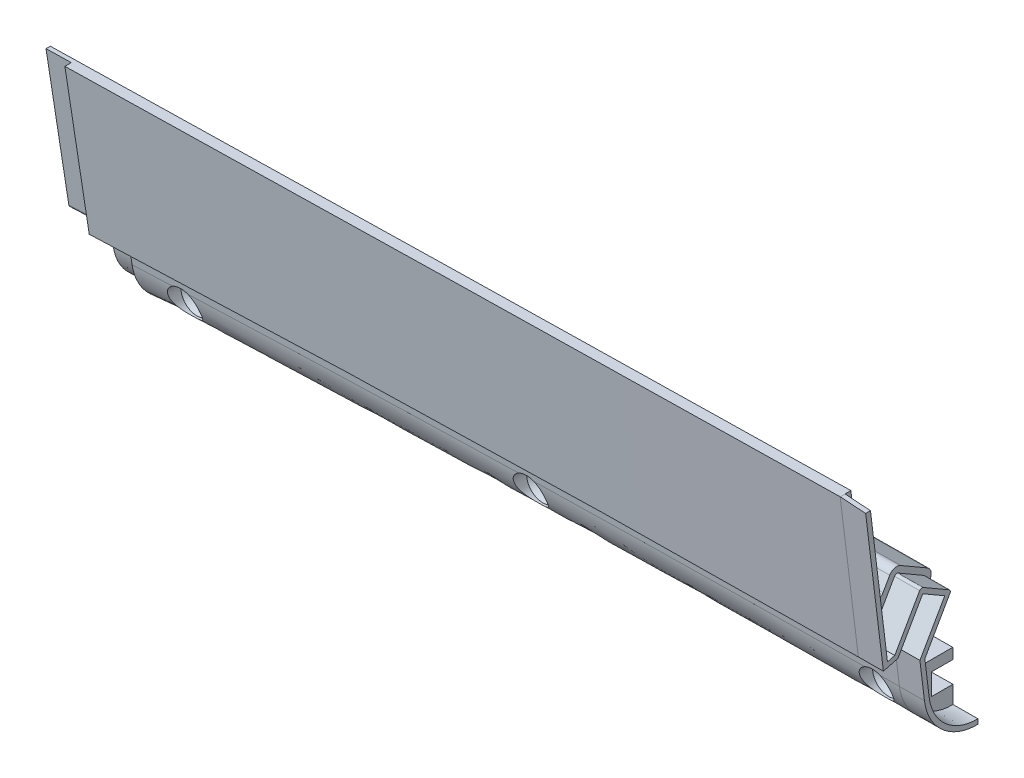
SolidWorks part; units mm, degrees
ref_plane "Front Plane" through (0, 0, 0) normal (0, 0, 1) x (1, 0, 0)
ref_plane "Top Plane" through (0, 0, 0) normal (0, 1, 0) x (1, 0, 0)
ref_plane "Right Plane" through (0, 0, 0) normal (1, 0, 0) x (0, 0, -1)
ref_plane "Plane3" through (-117.056, -3.871, 0) normal (0.9995, 0.0331, 0) x (0, 0, -1)
sketch "Sketch2" plane through (-117.056, -3.871, 0) normal (0.9995, 0.0331, 0) x (0, 0, -1)
  line L0 (-101.6, -41.1511) -> (-101.6, -45.9265)
  line L1 (-101.6, -41.1511) -> (-101.6, -45.9265)
  line L2 (-106.68, -45.9265) -> (-106.68, -50.6257)
  line L3 (-106.68, -45.9265) -> (-106.68, -50.6257)
  line L4 (-101.6, -50.6257) -> (-106.68, -50.6257)
  line L5 (-101.6, -50.6257) -> (-106.68, -50.6257)
  line L6 (-101.6, -50.6257) -> (-101.6, -56.1377)
  line L7 (-101.6, -50.6257) -> (-101.6, -56.1377)
  line L8 (-106.68, -45.9265) -> (-101.6, -45.9265)
  line L9 (-106.68, -45.9265) -> (-101.6, -45.9265)
  line L10 (-106.8705, -50.8162) -> (-108.9961, -53.9781) construction
  line L11 (-101.7905, -43.196) -> (-101.7905, -45.736)
  line L12 (-106.8705, -45.736) -> (-101.7905, -45.736)
  line L13 (-106.8705, -45.736) -> (-106.8705, -50.8162)
  line L14 (-101.7905, -50.8162) -> (-106.8705, -50.8162)
  line L15 (-101.7905, -50.8162) -> (-101.7905, -56.1377)
  line L16 (-101.7905, -43.196) -> (-101.6, -43.196)
  line L17 (-101.7905, -41.1511) -> (-101.7905, -45.736) construction
  line L18 (-120.8053, -33.0481) -> (-115.57, -36.0708)
  line L19 (-120.8053, -33.0481) -> (-115.57, -36.0708)
  line L20 (-109.601, -25.7318) -> (-114.8363, -22.709)
  line L21 (-109.601, -25.7318) -> (-114.8363, -22.709)
  line L22 (-114.8363, -22.709) -> (-120.8053, -33.0481)
  line L23 (-114.8363, -22.709) -> (-120.8053, -33.0481)
  line L24 (-115.57, -36.0708) -> (-109.601, -25.7318)
  line L25 (-115.57, -36.0708) -> (-109.601, -25.7318)
  line L26 (-115.57, -36.0708) -> (-114.523, -44.9291)
  line L28 (-118.1876, -34.5595) -> (-112.2186, -24.2204) construction
  line L29 (-114.6403, -39.5406) -> (-107.0838, -26.4518)
  line L30 (-107.7811, -23.8496) -> (-114.1162, -20.1918)
  line L31 (-116.7185, -20.8891) -> (-124.2749, -33.9778)
  line L33 (-106.1314, -24.8021) -> (-115.766, -19.2393) construction
  line L34 (-115.766, -19.2393) -> (-124.2749, -33.9778) construction
  line L35 (-114.6403, -39.5406) -> (-106.1314, -24.8021) construction
  line L36 (-124.2749, -33.9778) -> (-114.6403, -39.5406) construction
  line L37 (-112.9486, -36.6103) -> (-112.1701, -43.196)
  line L38 (-124.2749, -33.9778) -> (-128.0422, -2.1051)
  line L39 (-128.0422, -2.1051) -> (-132.6063, -0.4439)
  line L40 (-50.8, 0.7495) -> (-2184.4, 0.7495)
  line L41 (-125.822, 0.7495) -> (-133.442, 0.7495)
  line L42 (-122.1519, -30.3004) -> (-125.822, 0.7495)
  arc A0 (-114.523, -44.9291) -> (-101.7905, -56.1377) centre (-101.9108, -43.4383) ccw
  arc A2 (-114.1162, -20.1918) -> (-116.7185, -20.8891) centre (-115.0687, -21.8416) ccw
  arc A3 (-107.0838, -26.4518) -> (-107.7811, -23.8496) centre (-108.7336, -25.4993) ccw
  arc A4 (-133.442, 0.7495) -> (-132.6063, -0.4439) centre (-132.172, 0.7495) ccw
  point P41 (-133.442, 0.7495)
  dimension "D2" = 25.4
  dimension "D6" = 1.905
  dimension "D8" = 2.54
  dimension "D4" = 2.54
  dimension "D5" = 2.54
  dimension "D7" = 2.54
  dimension "D9" = 2.54
  dimension "D10" = 20
  dimension "D11" = 7.62
  dimension "D12" = 3.81
  dimension "D3" = 0.1905
sketch "Sketch3" plane through (0, 0, 101.6) normal (0, 0, 1) x (1, 0, 0)
  arc A0 (622.1039, -83.1998) -> (-622.1039, -83.1998) centre (0, -4954.4862) ccw construction
  arc A1 (622.1039, -83.1998) -> (-622.1039, -83.1998) centre (0, -4954.4862) ccw
sketch "Sketch4" plane through (-117.3306, 4.4304, 1117.6) normal (0.9995, 0.0331, 0) x (0, 0, -1)
  line L29 (1009.8189, -32.1556) -> (1003.4838, -28.4978) construction
  line L32 (1000.8815, -29.1951) -> (993.3251, -42.2838) construction
  line L35 (993.3251, -42.2838) -> (989.5578, -10.4111) construction
  line L50 (995.4481, -38.6064) -> (991.778, -7.5565) construction
  line L51 (1002.03, -44.3768) -> (1003.077, -53.235) construction
  line L52 (1015.8095, -59.1222) -> (1015.8095, -64.4437) construction
  line L53 (1015.8095, -59.1222) -> (1010.7295, -59.1222) construction
  line L54 (1010.7295, -54.042) -> (1010.7295, -59.1222) construction
  line L55 (1010.7295, -54.042) -> (1015.8095, -54.042) construction
  line L56 (1015.8095, -51.502) -> (1015.8095, -54.042) construction
  line L57 (1015.8095, -51.502) -> (1016, -51.502) construction
  line L58 (1004.6514, -44.9163) -> (1005.4299, -51.502) construction
  line L60 (1002.7637, -31.015) -> (996.7947, -41.3541) construction
  line L61 (1007.999, -34.0377) -> (1002.7637, -31.015) construction
  line L62 (1002.03, -44.3768) -> (1007.999, -34.0377) construction
  line L64 (991.5295, -5.4538) -> (988.9718, -5.4538)
  line L69 (1009.8189, -32.1556) -> (1003.4838, -28.4978)
  line L70 (1000.8815, -29.1951) -> (999.2724, -31.9822)
  line L71 (993.3251, -42.2838) -> (988.9718, -5.4538)
  line L74 (994.5502, -31.0104) -> (991.5295, -5.4538)
  line L75 (1002.03, -44.3768) -> (1003.077, -53.235)
  line L76 (1015.8095, -59.1222) -> (1015.8095, -64.4437)
  line L77 (1015.8095, -59.1222) -> (1010.7295, -59.1222)
  line L78 (1010.7295, -54.042) -> (1010.7295, -59.1222)
  line L79 (1010.7295, -54.042) -> (1015.8095, -54.042)
  line L80 (1015.8095, -51.502) -> (1015.8095, -54.042)
  line L81 (1015.8095, -51.502) -> (1007.6873, -51.502)
  line L82 (1004.7505, -45.7539) -> (1005.1649, -49.2601)
  line L84 (1002.7637, -31.015) -> (996.7947, -41.3541)
  line L85 (1007.999, -34.0377) -> (1002.7637, -31.015)
  line L86 (1002.03, -44.3768) -> (1007.999, -34.0377)
  line L87 (996.7947, -41.3541) -> (993.3251, -42.2838)
  line L88 (1005.0732, -44.1858) -> (1010.5162, -34.7578)
  arc A8 (1010.5162, -34.7578) -> (1009.8189, -32.1556) centre (1008.8664, -33.8053) ccw construction
  arc A9 (1003.4838, -28.4978) -> (1000.8815, -29.1951) centre (1002.5313, -30.1476) ccw construction
  arc A11 (1003.077, -53.235) -> (1015.8095, -64.4437) centre (1015.6892, -51.7443) ccw construction
  arc A12 (1010.5162, -34.7578) -> (1009.8189, -32.1556) centre (1008.8664, -33.8053) ccw
  arc A13 (1003.4838, -28.4978) -> (1000.8815, -29.1951) centre (1002.5313, -30.1476) ccw
  arc A15 (1003.077, -53.235) -> (1015.8095, -64.4437) centre (1015.6892, -51.7443) ccw
  arc A16 (1005.1649, -49.2601) -> (1007.6873, -51.502) centre (1007.6873, -48.962) ccw
  arc A17 (1004.7505, -45.7539) -> (1005.0732, -44.1858) centre (1007.2729, -45.4558) cw
  arc A18 (994.5502, -31.0104) -> (999.2724, -31.9822) centre (997.0727, -30.7122) ccw
  dimension "D2" = 2.54
  dimension "D1" = 36.83
sweep "Sweep3" add profiles "Sketch4" path "Sketch3"
sketch "Sketch5" plane through (0, 0, 101.7905) normal (0, 0, -1) x (-1, 0, 0)
  line L0 (211.6509, -4.1577) -> (0, -4954.4862) construction
  line L1 (0, -4954.4862) -> (26.7152, -2.7137) construction
  line L2 (117.0808, -1.0187) -> (0, -4954.4862) construction
  arc A1 (628.0925, -39.606) -> (-627.2635, -39.5001) centre (0, -4954.4862) ccw construction
  point P16 (117.0808, -1.0187)
ref_plane "Plane1" through (-211.4422, -9.0402, 0) normal (-0.9991, -0.0427, 0) x (0.0427, -0.9991, 0)
ref_plane "Plane2" through (-26.729, -0.1442, 0) normal (1, 0.0054, 0) x (-0.0054, 1, 0)
other "SurfaceCut1"
other "SurfaceCut2"
sketch "Sketch8" plane through (-117.056, -3.871, 0) normal (0.9995, 0.0331, 0) x (0, 0, -1)
  line L0 (-106.8705, -50.8162) -> (-106.8705, -45.736)
  line L1 (-106.8705, -50.8162) -> (-106.8705, -45.736)
  line L2 (-106.8705, -48.2761) -> (-119.5705, -48.2761)
  line L3 (-119.5705, -48.2761) -> (-119.5705, -44.4661)
  line L4 (-119.5705, -44.4661) -> (-110.6805, -44.4661)
  line L5 (-110.6805, -44.4661) -> (-108.7755, -46.3711)
  line L6 (-108.7755, -46.3711) -> (-106.8705, -46.3711)
  line L7 (-119.5705, -48.2761) -> (-117.7248, -48.2761) construction
  dimension "D1" = 1.905
  dimension "D2" = 1.905
  dimension "D3" = 12.7
  dimension "D4" = 45
  dimension "D5" = 3.81
revolve "Cut-Revolve1" cut sketch "Sketch8" angle 360 about L7
sketch "Sketch9" plane through (0, 0, 106.8705) normal (0, 0, -1) x (-1, 0, 0)
  line L0 (198.0737, -52.2212) -> (197.8686, -57.297) construction
  line L1 (32.934, -48.3318) -> (32.8999, -53.4117) construction
  arc A1 (209.5755, -52.6994) -> (26.4693, -48.2927) centre (0, -4954.4862) ccw construction
  arc A2 (209.3585, -57.7748) -> (26.4419, -53.3726) centre (0, -4954.4862) ccw construction
  point P8 (197.9712, -54.7591)
  point P11 (0, -4954.4862)
  point P16 (115.4604, -52.1207)
  dimension "D1" = 82.55
  dimension "D2" = 82.55
sketch "Sketch10" plane through (0, 0, 106.8705) normal (0, 0, -1) x (-1, 0, 0)
  line L0 (32.934, -48.3318) -> (32.8999, -53.4117) construction
  point P0 (32.917, -50.8717)
  point P1 (197.9712, -54.7591)
pattern_sketch "Sketch-Pattern1" of "Cut-Revolve1" driven by "Sketch10"
sketch "Sketch12" plane through (0, 0, 101.7905) normal (0, 0, -1) x (-1, 0, 0)
  line L0 (26.483, -45.7528) -> (0, -4954.4862) construction
  line L1 (0, -4954.4862) -> (20.514, -45.7243) construction
  arc A1 (209.684, -50.1619) -> (26.483, -45.7528) centre (0, -4954.4862) ccw construction
  arc A2 (26.483, -45.7528) -> (20.514, -45.7243) centre (0, -4954.4862) ccw
  dimension "D1" = 5.969
sketch "Sketch11" plane through (-26.729, -0.1442, 0) normal (1, 0.0054, 0) x (0, 0, -1)
  line L6 (-124.2749, -36.3915) -> (-128.6282, 0.4369) construction
  line L10 (-120.8053, -35.4619) -> (-124.2749, -36.3915) construction
  line L11 (-114.8363, -25.1233) -> (-120.8053, -35.4619) construction
  line L12 (-109.601, -28.1459) -> (-114.8363, -25.1233) construction
  line L14 (-115.57, -38.4845) -> (-109.601, -28.1459) construction
  line L15 (-114.523, -47.3423) -> (-115.57, -38.4845) construction
  line L16 (-124.2749, -36.3915) -> (-128.6282, 0.4369)
  line L17 (-120.8053, -35.4619) -> (-124.2749, -36.3915)
  line L18 (-114.8363, -25.1233) -> (-120.8053, -35.4619)
  line L25 (-109.601, -28.1459) -> (-114.8363, -25.1233)
  line L26 (-115.57, -38.4845) -> (-109.601, -28.1459)
  line L27 (-114.523, -47.3423) -> (-115.57, -38.4845)
  line L29 (-128.6282, 0.4369) -> (-126.0705, 0.4369) construction
  line L30 (-128.6282, 0.4369) -> (-127.4772, 0.4369)
  line L32 (-101.8013, -57.4075) -> (-101.7905, -57.4075)
  line L33 (-113.3879, -47.2081) -> (-114.3903, -38.7272)
  line L34 (-114.3903, -38.7272) -> (-108.3571, -28.2774)
  line L35 (-108.5896, -27.41) -> (-114.7047, -23.8794)
  line L54 (-115.5722, -24.1118) -> (-121.5584, -34.4803)
  line L55 (-121.5584, -34.4803) -> (-123.2949, -34.9456)
  line L56 (-123.2949, -34.9456) -> (-127.4772, 0.4369)
  line L57 (-123.2949, -34.9456) -> (-127.4931, 0.571) construction
  line L58 (-101.7905, -53.2292) -> (-101.7905, -58.5505) construction
  line L59 (-101.7905, -57.4075) -> (-101.7905, -58.5505)
  line L60 (-108.0396, -27.7275) -> (-115.2547, -23.5619) construction
  line L61 (-115.2547, -23.5619) -> (-121.5584, -34.4803) construction
  line L62 (-114.3903, -38.7272) -> (-108.0396, -27.7275) construction
  arc A3 (-114.7047, -23.8794) -> (-115.5722, -24.1118) centre (-115.0222, -24.4293) ccw
  arc A4 (-108.3571, -28.2774) -> (-108.5896, -27.41) centre (-108.9071, -27.9599) ccw
  spline S0 degree 3 poles (369.46, 1883.5075) (53.4107, 251.0182) (-51.656, -67.534) (-104.4782, -58.2948) (-104.8546, -58.2112) (-105.6018, -58.009) (-105.9744, -57.8897) (-107.0674, -57.4831) (-107.762, -57.1492) (-108.7542, -56.5565) (-109.0766, -56.3436) (-109.7043, -55.8862) (-110.0099, -55.6412) (-110.8822, -54.8736) (-111.4114, -54.3143) (-112.3662, -53.1018) (-112.7943, -52.4418) (-113.513, -51.074) (-113.8076, -50.3629) (-114.1523, -49.255) (-114.2511, -48.8776) (-128.7728, 19.3257) (415.3179, 185.4439) (1806.7101, 500.6793) knots -8.519335 -8.519335 -8.519335 -8.519335 0.125 0.125 0.1875 0.1875 0.25 0.25 0.375 0.375 0.4375 0.4375 0.5 0.5 0.625 0.625 0.75 0.75 0.875 0.875 0.9375 0.9375 12.048429 12.048429 12.048429 12.048429 only from (-101.7905, -58.5505) to (-114.523, -47.3423) construction
  spline S1 degree 3 poles (-101.7905, -58.5505) (-102.5713, -58.5579) (-103.3407, -58.4937) (-104.4782, -58.2948) (-104.8546, -58.2112) (-105.6018, -58.009) (-105.9744, -57.8897) (-107.0674, -57.4831) (-107.762, -57.1492) (-108.7542, -56.5565) (-109.0766, -56.3436) (-109.7043, -55.8862) (-110.0099, -55.6412) (-110.8822, -54.8736) (-111.4114, -54.3143) (-112.3662, -53.1018) (-112.7943, -52.4418) (-113.513, -51.074) (-113.8076, -50.3629) (-114.1523, -49.255) (-114.2511, -48.8776) (-114.4136, -48.1146) (-114.4771, -47.73) (-114.523, -47.3423) knots 0 0 0 0 0.125 0.125 0.1875 0.1875 0.25 0.25 0.375 0.375 0.4375 0.4375 0.5 0.5 0.625 0.625 0.75 0.75 0.875 0.875 0.9375 0.9375 1 1 1 1
  spline S2 degree 1 poles (-101.8013, -57.4075) (-113.3879, -47.2081) knots 0 0 1 1 construction
  spline S3 degree 3 poles (-101.8013, -57.4075) (-103.2019, -57.4208) (-106.0351, -56.9259) (-109.7159, -54.7251) (-111.9316, -51.9017) (-113.0054, -49.3109) (-113.3048, -47.9109) (-113.3879, -47.2081) knots 0 0 0 0 0.25 0.5 0.75 0.875 1 1 1 1
  dimension "D2" = 0.635
  dimension "D1" = 1.143
sweep "Sweep4" add profiles "Sketch11" path "Sketch12"
sketch "Sketch14" plane through (-211.4422, -9.0402, 0) normal (-0.9991, -0.0427, 0) x (0, 0, 1)
  line L0 (113.0095, -42.7133) -> (113.9971, -34.3581)
  line L1 (113.9971, -34.3581) -> (107.5192, -23.138)
  line L2 (107.5192, -23.138) -> (115.3941, -18.5914)
  line L3 (115.3941, -18.5914) -> (121.8095, -29.7031)
  line L4 (121.8095, -29.7031) -> (122.9682, -30.0136)
  line L5 (122.9682, -30.0136) -> (127.1147, 5.0658)
  line L18 (128.6282, 4.8869) -> (126.0705, 4.8869)
  line L19 (126.0705, 4.8869) -> (123.0498, -20.6686)
  line L20 (118.3276, -21.6403) -> (116.7185, -18.8534)
  line L21 (114.1162, -18.1561) -> (107.7811, -21.8137)
  line L22 (107.0838, -24.4158) -> (112.5268, -33.8434)
  line L23 (112.8495, -35.4115) -> (112.4351, -38.9175)
  line L24 (109.9127, -41.1592) -> (101.7905, -41.1592)
  line L25 (101.7905, -41.1592) -> (101.7905, -43.6991)
  line L26 (101.7905, -43.6991) -> (106.8705, -43.6991)
  line L27 (106.8705, -43.6991) -> (106.8705, -48.7791)
  line L28 (106.8705, -48.7791) -> (101.7905, -48.7791)
  line L29 (101.7905, -48.7791) -> (101.7905, -54.1004)
  line L30 (114.523, -42.8922) -> (115.57, -34.0344)
  line L31 (115.57, -34.0344) -> (109.601, -23.6958)
  line L32 (109.601, -23.6958) -> (114.8363, -20.6732)
  line L33 (114.8363, -20.6732) -> (120.8053, -31.0118)
  line L34 (120.8053, -31.0118) -> (124.2749, -31.9414)
  line L35 (124.2749, -31.9414) -> (128.6282, 4.8869)
  line L36 (128.6282, 4.8869) -> (126.0705, 4.8869)
  line L37 (126.0705, 4.8869) -> (123.0498, -20.6686)
  line L38 (118.3276, -21.6403) -> (116.7185, -18.8534)
  line L39 (114.1162, -18.1561) -> (107.7811, -21.8137)
  line L40 (107.0838, -24.4158) -> (112.5268, -33.8434)
  line L41 (112.8495, -35.4115) -> (112.4351, -38.9175)
  line L42 (109.9127, -41.1592) -> (101.7905, -41.1592)
  line L43 (101.7905, -41.1592) -> (101.7905, -43.6991)
  line L44 (101.7905, -43.6991) -> (106.8705, -43.6991)
  line L45 (106.8705, -43.6991) -> (106.8705, -48.7791)
  line L46 (106.8705, -48.7791) -> (101.7905, -48.7791)
  line L47 (101.7905, -48.7791) -> (101.7905, -54.1004)
  line L48 (114.523, -42.8922) -> (115.57, -34.0344)
  line L49 (115.57, -34.0344) -> (109.601, -23.6958)
  line L50 (109.601, -23.6958) -> (114.8363, -20.6732)
  line L51 (114.8363, -20.6732) -> (120.8053, -31.0118)
  line L52 (120.8053, -31.0118) -> (124.2749, -31.9414)
  line L53 (124.2749, -31.9414) -> (128.6282, 4.8869)
  arc A4 (116.7185, -18.8534) -> (114.1162, -18.1561) centre (115.0687, -19.8059) ccw
  arc A5 (107.7811, -21.8137) -> (107.0838, -24.4158) centre (108.7335, -23.4634) ccw
  arc A6 (112.8495, -35.4115) -> (112.5268, -33.8434) centre (110.3273, -35.1133) ccw
  arc A7 (109.9127, -41.1592) -> (112.4351, -38.9175) centre (109.9127, -38.6193) ccw
  arc A8 (116.7185, -18.8534) -> (114.1162, -18.1561) centre (115.0687, -19.8059) ccw
  arc A9 (107.7811, -21.8137) -> (107.0838, -24.4158) centre (108.7335, -23.4634) ccw
  arc A10 (112.8495, -35.4115) -> (112.5268, -33.8434) centre (110.3273, -35.1133) ccw
  arc A11 (109.9127, -41.1592) -> (112.4351, -38.9175) centre (109.9127, -38.6193) ccw
  spline S0 degree 1 poles (101.8049, -52.5765) (113.0095, -42.7133) knots 0 0 1 1 construction
  spline S1 degree 3 poles (101.8049, -52.5765) (102.4893, -52.583) (103.8689, -52.4674) (106.4858, -51.7551) (109.4658, -49.9761) (112.0284, -46.7154) (112.8505, -44.0584) (113.0095, -42.7133) knots 0 0 0 0 0.125 0.25 0.5 0.75 1 1 1 1
  spline S2 degree 3 poles (-1420.2451, -2589.1907) (7.5348, 76.4537) (129.3579, -7.252) (122.7249, -21.671) (122.575, -21.8961) (122.2185, -22.2837) (122.0069, -22.4517) (121.6628, -22.6462) (121.5435, -22.702) (121.2955, -22.795) (121.1665, -22.8321) (120.908, -22.8851) (120.7774, -22.9014) (120.5134, -22.9137) (120.3791, -22.9094) (120.1163, -22.8803) (119.987, -22.8557) (119.7325, -22.7864) (119.6063, -22.7412) (119.2436, -22.578) (119.0214, -22.433) (93.7379, 0.421) (581.1886, 448.0858) (2362.312, 1968.4478) knots -7.286241 -7.286241 -7.286241 -7.286241 0.125 0.125 0.25 0.25 0.375 0.375 0.4375 0.4375 0.5 0.5 0.5625 0.5625 0.625 0.625 0.6875 0.6875 0.75 0.75 0.875 0.875 16.766809 16.766809 16.766809 16.766809 only from (123.0498, -20.6686) to (118.3276, -21.6403)
  spline S3 degree 3 poles (-288.3388, 2916.9987) (-102.777, 757.3692) (19.5454, -60.9671) (103.3479, -54.0254) (103.7348, -53.9753) (104.8774, -53.7738) (105.6202, -53.5717) (107.068, -53.0324) (107.777, -52.6914) (109.1008, -51.8981) (109.7227, -51.4442) (110.5948, -50.6762) (110.8766, -50.4042) (111.4099, -49.8396) (111.662, -49.5468) (112.3757, -48.6378) (112.795, -47.9912) (113.3369, -46.9586) (113.5026, -46.6041) (113.7979, -45.8886) (113.9285, -45.5258) (132.5439, 14.5864) (-288.4354, 203.7302) (-2703.1014, 979.8882) knots -13.349036 -13.349036 -13.349036 -13.349036 0.0625 0.0625 0.125 0.125 0.25 0.25 0.375 0.375 0.5 0.5 0.5625 0.5625 0.625 0.625 0.75 0.75 0.8125 0.8125 0.875 0.875 11.030088 11.030088 11.030088 11.030088 only from (101.7905, -54.1004) to (114.523, -42.8922)
  spline S4 degree 3 poles (123.0498, -20.6686) (123.0184, -20.9338) (122.9449, -21.1927) (122.7249, -21.671) (122.575, -21.8961) (122.2185, -22.2837) (122.0069, -22.4517) (121.6628, -22.6462) (121.5435, -22.702) (121.2955, -22.795) (121.1665, -22.8321) (120.908, -22.8851) (120.7774, -22.9014) (120.5134, -22.9137) (120.3791, -22.9094) (120.1163, -22.8803) (119.987, -22.8557) (119.7325, -22.7864) (119.6063, -22.7412) (119.2436, -22.578) (119.0214, -22.433) (118.6267, -22.0763) (118.4611, -21.8716) (118.3276, -21.6403) knots 0 0 0 0 0.125 0.125 0.25 0.25 0.375 0.375 0.4375 0.4375 0.5 0.5 0.5625 0.5625 0.625 0.625 0.6875 0.6875 0.75 0.75 0.875 0.875 1 1 1 1
  spline S5 degree 3 poles (101.7905, -54.1004) (102.1809, -54.1041) (102.5705, -54.0898) (103.3479, -54.0254) (103.7348, -53.9753) (104.8774, -53.7738) (105.6202, -53.5717) (107.068, -53.0324) (107.777, -52.6914) (109.1008, -51.8981) (109.7227, -51.4442) (110.5948, -50.6762) (110.8766, -50.4042) (111.4099, -49.8396) (111.662, -49.5468) (112.3757, -48.6378) (112.795, -47.9912) (113.3369, -46.9586) (113.5026, -46.6041) (113.7979, -45.8886) (113.9285, -45.5258) (114.2702, -44.4227) (114.4313, -43.6677) (114.523, -42.8922) knots 0 0 0 0 0.0625 0.0625 0.125 0.125 0.25 0.25 0.375 0.375 0.5 0.5 0.5625 0.5625 0.625 0.625 0.75 0.75 0.8125 0.8125 0.875 0.875 1 1 1 1
  dimension "D1" = 0
  dimension "D2" = 1.524
sketch "Sketch15" plane through (-211.4422, -9.0402, 0) normal (-0.9991, -0.0427, 0) x (0, 0, 1)
  line L0 (113.0095, -42.7133) -> (113.9971, -34.3581) construction
  line L1 (113.9971, -34.3581) -> (107.5192, -23.138) construction
  line L2 (107.5192, -23.138) -> (115.3941, -18.5914) construction
  line L3 (115.3941, -18.5914) -> (121.8095, -29.7031) construction
  line L4 (121.8095, -29.7031) -> (122.9682, -30.0136) construction
  line L5 (122.9682, -30.0136) -> (127.1147, 5.0658) construction
  line L6 (113.0095, -42.7133) -> (113.9724, -34.5675)
  line L7 (113.8917, -34.1755) -> (107.5192, -23.138)
  line L8 (107.5192, -23.138) -> (115.3941, -18.5914)
  line L9 (115.3941, -18.5914) -> (121.678, -29.4753)
  line L10 (122.0636, -29.7712) -> (122.2594, -29.8237)
  line L11 (123.0543, -29.2848) -> (127.0936, 4.8869)
  line L12 (101.7905, -48.7791) -> (101.7905, -54.1004) construction
  line L13 (101.7905, -48.7791) -> (101.7905, -52.5765)
  line L14 (101.8049, -52.5765) -> (101.7905, -52.5765)
  line L18 (124.2749, -31.9414) -> (128.6282, 4.8869)
  line L19 (128.6282, 4.8869) -> (126.0705, 4.8869)
  line L20 (126.0705, 4.8869) -> (123.0498, -20.6686)
  line L21 (118.3276, -21.6403) -> (116.7185, -18.8534)
  line L22 (114.1162, -18.1561) -> (107.7811, -21.8137)
  line L23 (107.0838, -24.4158) -> (112.5268, -33.8434)
  line L24 (112.8495, -35.4115) -> (112.4351, -38.9175)
  line L25 (109.9127, -41.1592) -> (101.7905, -41.1592)
  line L26 (101.7905, -41.1592) -> (101.7905, -43.6991)
  line L27 (101.7905, -43.6991) -> (106.8705, -43.6991)
  line L28 (106.8705, -43.6991) -> (106.8705, -48.7791)
  line L29 (106.8705, -48.7791) -> (101.7905, -48.7791)
  line L30 (101.7905, -48.7791) -> (101.7905, -54.1004)
  line L31 (114.523, -42.8922) -> (115.57, -34.0344)
  line L32 (115.57, -34.0344) -> (109.601, -23.6958)
  line L33 (109.601, -23.6958) -> (114.8363, -20.6732)
  line L34 (114.8363, -20.6732) -> (120.8053, -31.0118)
  line L35 (120.8053, -31.0118) -> (124.2749, -31.9414)
  line L37 (127.0936, 4.8869) -> (126.0705, 4.8869)
  line L38 (126.0705, 4.8869) -> (123.0498, -20.6686)
  line L39 (118.3276, -21.6403) -> (116.7185, -18.8534)
  line L40 (114.1162, -18.1561) -> (107.7811, -21.8137)
  line L41 (107.0838, -24.4158) -> (112.5268, -33.8434)
  line L42 (112.8495, -35.4115) -> (112.4351, -38.9175)
  line L43 (109.9127, -41.1592) -> (101.7905, -41.1592)
  line L44 (101.7905, -41.1592) -> (101.7905, -43.6991)
  line L45 (101.7905, -43.6991) -> (106.8705, -43.6991)
  line L46 (106.8705, -43.6991) -> (106.8705, -48.7791)
  line L47 (106.8705, -48.7791) -> (101.7905, -48.7791)
  arc A0 (113.9724, -34.5675) -> (113.8917, -34.1755) centre (113.3418, -34.493) ccw
  arc A1 (121.678, -29.4753) -> (122.0636, -29.7712) centre (122.2279, -29.1578) ccw
  arc A2 (122.2594, -29.8237) -> (123.0543, -29.2848) centre (122.4237, -29.2103) ccw
  arc A4 (116.7185, -18.8534) -> (114.1162, -18.1561) centre (115.0687, -19.8059) ccw
  arc A5 (107.7811, -21.8137) -> (107.0838, -24.4158) centre (108.7335, -23.4634) ccw
  arc A6 (112.8495, -35.4115) -> (112.5268, -33.8434) centre (110.3273, -35.1133) ccw
  arc A7 (109.9127, -41.1592) -> (112.4351, -38.9175) centre (109.9127, -38.6193) ccw
  arc A8 (116.7185, -18.8534) -> (114.1162, -18.1561) centre (115.0687, -19.8059) ccw
  arc A9 (107.7811, -21.8137) -> (107.0838, -24.4158) centre (108.7335, -23.4634) ccw
  arc A10 (112.8495, -35.4115) -> (112.5268, -33.8434) centre (110.3273, -35.1133) ccw
  arc A11 (109.9127, -41.1592) -> (112.4351, -38.9175) centre (109.9127, -38.6193) ccw
  spline S0 degree 3 poles (1969.6766, 654.3437) (8.5109, 56.766) (75.3403, -60.2329) (106.4858, -51.7551) (109.4658, -49.9761) (134.2797, -18.4018) (-16.091, 107.1074) (-926.156, -1745.3361) knots -5.450838 -5.450838 -5.450838 -5.450838 0.125 0.25 0.5 0.75 7.512309 7.512309 7.512309 7.512309 only from (101.8049, -52.5765) to (113.0095, -42.7133) construction
  spline S1 degree 3 poles (101.8049, -52.5765) (102.4893, -52.583) (103.8689, -52.4674) (106.4858, -51.7551) (109.4658, -49.9761) (112.0284, -46.7154) (112.8505, -44.0584) (113.0095, -42.7133) knots 0 0 0 0 0.125 0.25 0.5 0.75 1 1 1 1
  spline S2 degree 3 poles (-1420.2451, -2589.1907) (7.5348, 76.4537) (129.3579, -7.252) (122.7249, -21.671) (122.575, -21.8961) (122.2185, -22.2837) (122.0069, -22.4517) (121.6628, -22.6462) (121.5435, -22.702) (121.2955, -22.795) (121.1665, -22.8321) (120.908, -22.8851) (120.7774, -22.9014) (120.5134, -22.9137) (120.3791, -22.9094) (120.1163, -22.8803) (119.987, -22.8557) (119.7325, -22.7864) (119.6063, -22.7412) (119.2436, -22.578) (119.0214, -22.433) (93.7379, 0.421) (581.1886, 448.0858) (2362.312, 1968.4478) knots -7.286241 -7.286241 -7.286241 -7.286241 0.125 0.125 0.25 0.25 0.375 0.375 0.4375 0.4375 0.5 0.5 0.5625 0.5625 0.625 0.625 0.6875 0.6875 0.75 0.75 0.875 0.875 16.766809 16.766809 16.766809 16.766809 only from (123.0498, -20.6686) to (118.3276, -21.6403)
  spline S3 degree 3 poles (-93.3253, 926.6784) (-10.5613, 232.0775) (53.1389, -58.1844) (103.3479, -54.0254) (103.7348, -53.9753) (104.8774, -53.7738) (105.6202, -53.5717) (107.068, -53.0324) (107.777, -52.6914) (109.1008, -51.8981) (109.7227, -51.4442) (110.5948, -50.6762) (110.8766, -50.4042) (111.4099, -49.8396) (111.662, -49.5468) (112.3757, -48.6378) (112.795, -47.9912) (113.3369, -46.9586) (113.5026, -46.6041) (113.7979, -45.8886) (113.9285, -45.5258) (125.9187, -6.8076) (-43.2917, 84.8615) (-804.6708, 350.8867) knots -7.947776 -7.947776 -7.947776 -7.947776 0.0625 0.0625 0.125 0.125 0.25 0.25 0.375 0.375 0.5 0.5 0.5625 0.5625 0.625 0.625 0.75 0.75 0.8125 0.8125 0.875 0.875 7.39364 7.39364 7.39364 7.39364 only from (101.7905, -54.1004) to (114.523, -42.8922)
  spline S4 degree 3 poles (123.0498, -20.6686) (123.0184, -20.9338) (122.9449, -21.1927) (122.7249, -21.671) (122.575, -21.8961) (122.2185, -22.2837) (122.0069, -22.4517) (121.6628, -22.6462) (121.5435, -22.702) (121.2955, -22.795) (121.1665, -22.8321) (120.908, -22.8851) (120.7774, -22.9014) (120.5134, -22.9137) (120.3791, -22.9094) (120.1163, -22.8803) (119.987, -22.8557) (119.7325, -22.7864) (119.6063, -22.7412) (119.2436, -22.578) (119.0214, -22.433) (118.6267, -22.0763) (118.4611, -21.8716) (118.3276, -21.6403) knots 0 0 0 0 0.125 0.125 0.25 0.25 0.375 0.375 0.4375 0.4375 0.5 0.5 0.5625 0.5625 0.625 0.625 0.6875 0.6875 0.75 0.75 0.875 0.875 1 1 1 1
  dimension "D2" = 0.635
  dimension "D1" = 0
sketch "Sketch16" plane through (0, 0, 101.7905) normal (0, 0, -1) x (-1, 0, 0)
  arc A0 (215.6474, -50.4205) -> (209.684, -50.1619) centre (0, -4954.4862) ccw
  arc A1 (209.684, -50.1619) -> (26.483, -45.7528) centre (0, -4954.4862) ccw construction
  dimension "D1" = 5.969
sweep "Sweep5" add profiles "Sketch15" path "Sketch16"
ref_plane "Plane4" through (0.0176, -0.9462, 0) normal (0.0186, -0.9998, 0) x (-0.9998, -0.0186, 0)
other "SurfaceCut3"
ref_plane "Plane5" through (-0.2814, -3.5408, 0) normal (-0.0792, -0.9969, 0) x (-0.9969, 0.0792, 0)
other "SurfaceCut4"
